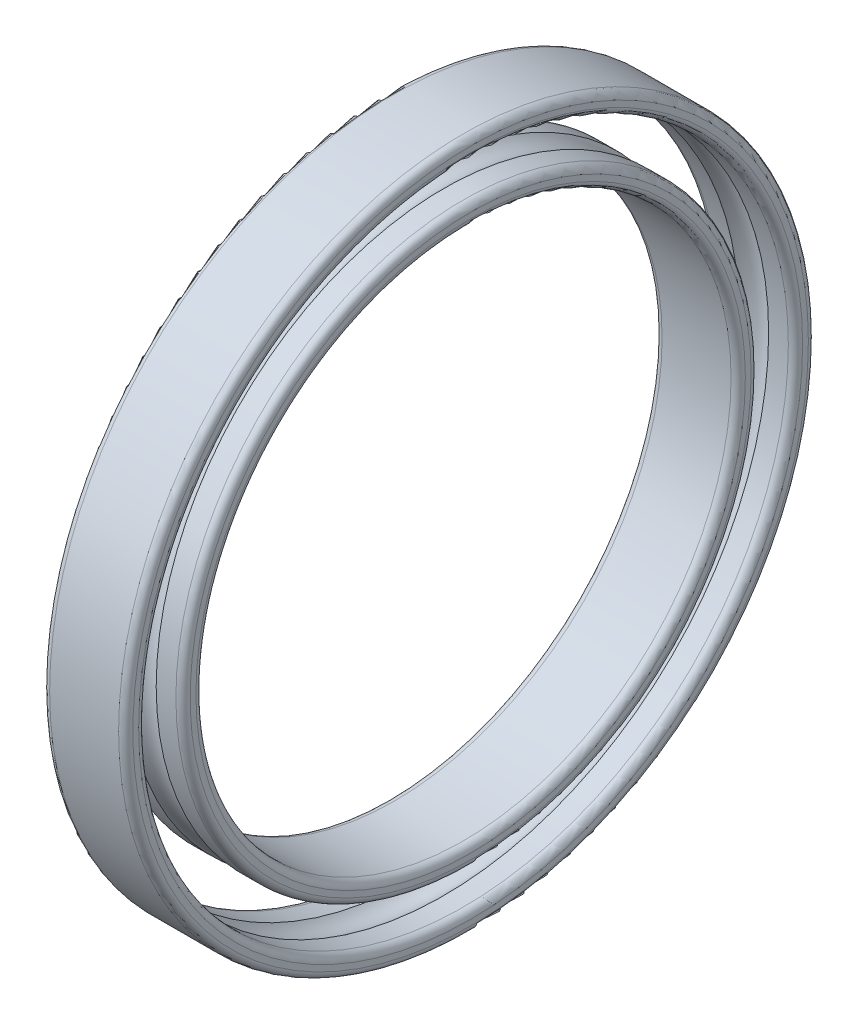
SolidWorks part; units mm, degrees
ref_plane "Front Plane" through (0, 0, 0) normal (0, 0, 1) x (1, 0, 0)
ref_plane "Top Plane" through (0, 0, 0) normal (0, 1, 0) x (1, 0, 0)
ref_plane "Right Plane" through (0, 0, 0) normal (1, 0, 0) x (0, 0, -1)
sketch "Sketch1" plane through (0, 0, 0) normal (0, 0, 1) x (1, 0, 0)
  line L0 (0, 0) -> (0, 29) construction
  line L1 (-3.5, 29) -> (3.5, 29)
  line L2 (-3.5, 29) -> (-3.5, 27.3157)
  line L3 (-3.5, 22.5) -> (3.5, 22.5)
  line L4 (3.5, 29) -> (3.5, 27.3157)
  line L5 (-3.5, 29) -> (3.5, 22.5) construction
  line L6 (-3.5, 22.5) -> (3.5, 29) construction
  line L7 (9.4783, 0) -> (9.4783, 22.5) construction
  line L8 (1.2444, 27.3157) -> (3.5, 27.3157)
  line L9 (-3.5, 27.3157) -> (-1.2444, 27.3157)
  line L11 (-3.5, 24.1843) -> (-1.2444, 24.1843)
  line L13 (-3.5, 27.3157) -> (3.5, 24.1843) construction
  line L14 (-3.5, 24.1843) -> (3.5, 27.3157) construction
  line L15 (1.2444, 24.1843) -> (3.5, 24.1843)
  line L16 (-3.5, 24.1843) -> (-3.5, 22.5)
  line L17 (3.5, 24.1843) -> (3.5, 22.5)
  line L18 (0, -0.3811) -> (0, 0) construction
  line L19 (0, 0) -> (-16.4928, 0) construction
  arc A0 (-1.2444, 24.1843) -> (1.2444, 24.1843) centre (0, 25.75) ccw
  arc A1 (1.2444, 27.3157) -> (-1.2444, 27.3157) centre (0, 25.75) ccw
  point P0 (0, 25.75)
  dimension "D4" = 4
  dimension "D1" = 7
  dimension "D2" = 29
  dimension "D3" = 6.5
  dimension "D5" = 22.5
revolve "Revolve1" add sketch "Sketch1" angle 360 about L19
fillet "Fillet1" radius 0.6 3 edges at (3.5, 0, -29) (-3.5, 0, -27.3157) (3.5, 0, -27.3157)
fillet "Fillet2" radius 0.6 1 edges at (-3.5, 0, -29)
fillet "Fillet3" radius 0.6 4 edges at (-3.5, 0, -24.1843) (-3.5, 0, -22.5) (3.5, 0, -24.1843) (3.5, 0, -22.5)
